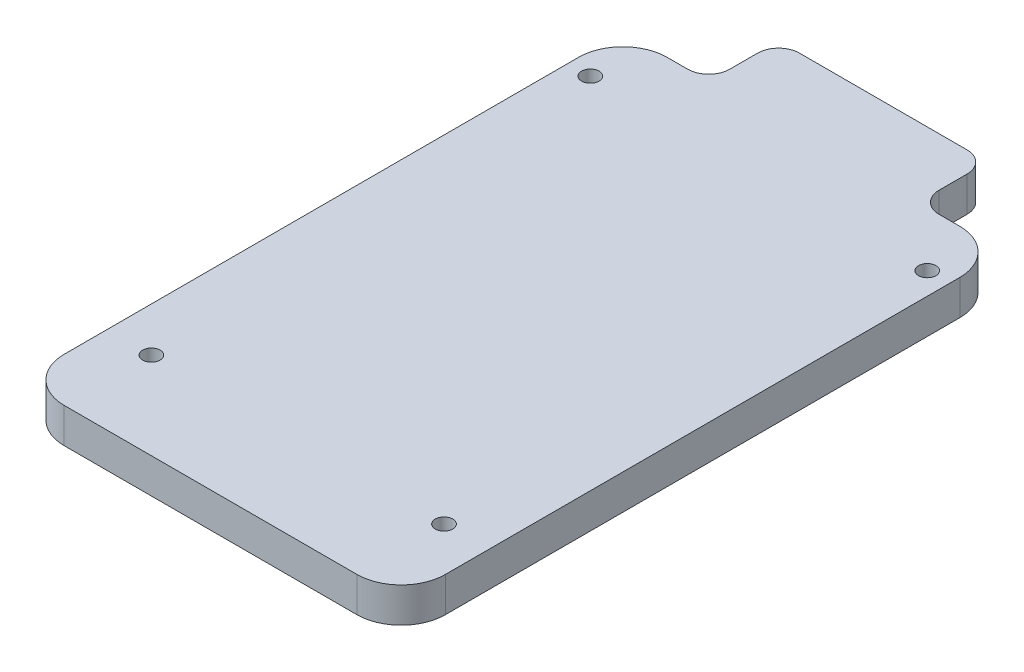
SolidWorks part; units mm, degrees
ref_plane "Front Plane" through (0, 0, 0) normal (0, 0, 1) x (1, 0, 0)
ref_plane "Top Plane" through (0, 0, 0) normal (0, 1, 0) x (1, 0, 0)
ref_plane "Right Plane" through (0, 0, 0) normal (1, 0, 0) x (0, 0, -1)
sketch "Sketch1" plane through (0, 0, 0) normal (0, 1, 0) x (1, 0, 0)
  line L0 (-24.13, 35.3454) -> (24.13, 35.3454) construction
  line L1 (24.13, 35.3454) -> (20.955, -30.6946) construction
  line L2 (20.955, -30.6946) -> (-20.955, -30.6946) construction
  line L3 (-20.955, -30.6946) -> (-24.13, 35.3454) construction
  line L4 (-24.13, 35.3454) -> (20.955, -30.6946) construction
  line L5 (24.13, 35.3454) -> (-20.955, -30.6946) construction
  line L7 (20.955, -43.18) -> (-20.955, -43.18)
  line L8 (27.305, -36.83) -> (27.305, 36.83)
  line L9 (20.955, 43.18) -> (-20.955, 43.18)
  line L10 (-27.305, -36.83) -> (-27.305, 36.83)
  line L11 (27.305, -43.18) -> (-27.305, 43.18) construction
  line L12 (27.305, 43.18) -> (-27.305, -43.18) construction
  arc A0 (-20.955, -43.18) -> (-27.305, -36.83) centre (-20.955, -36.83) cw
  arc A1 (20.955, -43.18) -> (27.305, -36.83) centre (20.955, -36.83) ccw
  arc A2 (27.305, 36.83) -> (20.955, 43.18) centre (20.955, 36.83) ccw
  arc A3 (-20.955, 43.18) -> (-27.305, 36.83) centre (-20.955, 36.83) ccw
  point P2 (0, 0)
  point P9 (0, 0)
  dimension "D6" = 6.35
  dimension "D1" = 48.26
  dimension "D2" = 41.91
  dimension "D3" = 66.04
  dimension "D4" = 86.36
  dimension "D5" = 54.61
extrude "Boss-Extrude1" add sketch "Sketch1" along normal blind 5
hole_wizard "Tap Drill for M3x0.5 Tap1" positions "Sketch3" profile "Sketch4" hole size "M3x0.5" standard "ANSI Metric" end condition up to next
sketch "Sketch3" plane through (0, 5, 0) normal (0, 1, 0) x (1, 0, 0)
  point P0 (-24.13, 35.3454)
  point P2 (24.13, 35.3454)
  point P4 (-20.955, -30.6946)
  point P6 (20.955, -30.6946)
sketch "Sketch4" plane through (-24.13, 5, -35.3454) normal (1, 0, 0) x (0, 0, 1)
  line L0 (0, 0) -> (0, 5)
  line L1 (0, 5) -> (1.25, 5)
  line L2 (1.25, 5) -> (1.25, 0)
  line L5 (1.25, 0) -> (0, 0)
  line L11 (0, -6.35) -> (0, 107.95) construction
  dimension "Thru Hole Dia." = 2.5
  dimension "Thru Hole Depth" = 5
sketch "Sketch5" plane through (0, 5, 0) normal (0, 1, 0) x (1, 0, 0)
  line L0 (20.955, 43.18) -> (-20.955, 43.18) construction
  line L1 (-15, 43.18) -> (15, 43.18)
  line L2 (-15, 43.18) -> (-15, 53.18)
  line L3 (-15, 53.18) -> (15, 53.18)
  line L4 (15, 43.18) -> (15, 53.18)
  point P6 (0, 43.18)
  dimension "D1" = 30
  dimension "D2" = 10
extrude "Boss-Extrude2" add sketch "Sketch5" against normal blind 5
fillet "Fillet1" radius 3 4 edges at (15, 2.5, -43.18) (15, 2.5, -53.18) (-15, 2.5, -53.18) (-15, 2.5, -43.18)
sketch "Sketch6" plane through (0, 0, -53.18) normal (0, 0, -1) x (-1, 0, 0)
  line L0 (12, 1.5) -> (-12, 1.5) construction
  line L1 (12, 0) -> (12, 5) construction
  line L3 (-12, 0) -> (12, 0) construction
  line L4 (-12, 5) -> (-12, 0) construction
  point P6 (8, 1.5)
  point P7 (-8, 1.5)
  point P8 (12, 1.5)
  point P10 (-12, 1.5)
  dimension "D1" = 4
  dimension "D2" = 4
  dimension "D3" = 1.5
hole_wizard "Tap Drill for M3x0.5 Tap2" positions "Sketch7" profile "Sketch9" hole size "M3x0.5" standard "ANSI Metric"
sketch "Sketch7" plane through (0, 0, -53.18) normal (0, 0, -1) x (-1, 0, 0)
  point P0 (8, 1.5)
  point P3 (-8, 1.5)
sketch "Sketch9" plane through (-8, 1.5, -53.18) normal (1, 0, 0) x (0, 1, 0)
  line L0 (0, 0) -> (0, 5.7511)
  line L1 (0, 5.7511) -> (1.25, 5)
  line L2 (1.25, 5) -> (1.25, 0)
  line L5 (1.25, 0) -> (0, 0)
  line L10 (0, 5.7511) -> (-1.25, 5) construction
  line L11 (0, -6.35) -> (0, 107.95) construction
  dimension "Hole Dia." = 2.5
  dimension "Hole Depth" = 5
  dimension "Drill Angle" = 118
